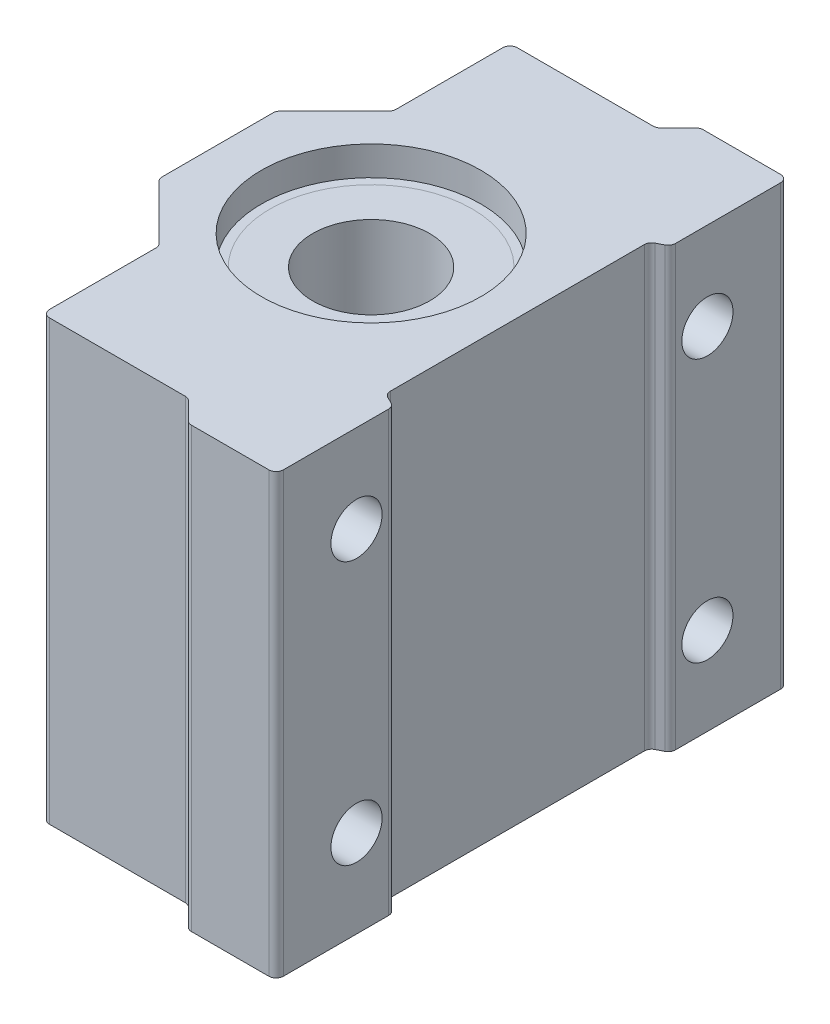
SolidWorks part; units mm, degrees
ref_plane "Front Plane" through (0, 0, 0) normal (0, 0, 1) x (1, 0, 0)
ref_plane "Top Plane" through (0, 0, 0) normal (0, 1, 0) x (1, 0, 0)
ref_plane "Right Plane" through (0, 0, 0) normal (1, 0, 0) x (0, 0, -1)
sketch "Sketch1" plane through (0, 0, 0) normal (0, 1, 0) x (1, 0, 0)
  line L0 (-2.4565, 16.1957) -> (3.5435, 16.1957)
  line L1 (-2.4565, 16.1957) -> (-2.4565, 14.6957) construction
  line L2 (-2.4565, 14.6957) -> (-3.9565, 14.6957) construction
  line L3 (-3.9565, 14.6957) -> (-2.4565, 16.1957)
  line L4 (-3.9565, 14.6957) -> (-13.9565, 14.6957)
  line L5 (-13.9565, 14.6957) -> (-13.9565, 6.6957)
  line L6 (-13.9565, 6.6957) -> (-17.9565, 6.6957) construction
  line L7 (-17.9565, 6.6957) -> (-17.9565, 2.6957) construction
  line L8 (-13.9565, 6.6957) -> (-17.9565, 2.6957)
  line L9 (-17.9565, 2.6957) -> (-17.9565, -5.3043)
  line L10 (-17.9565, -5.3043) -> (-17.9565, -9.3043) construction
  line L11 (-17.9565, -9.3043) -> (-13.9565, -9.3043) construction
  line L12 (-17.9565, -5.3043) -> (-13.9565, -9.3043)
  line L13 (-13.9565, -9.3043) -> (-13.9565, -17.3043)
  line L14 (-13.9565, -17.3043) -> (-3.9565, -17.3043)
  line L15 (-3.9565, -17.3043) -> (-3.9565, -18.8043)
  line L16 (-3.9565, -18.8043) -> (-2.4565, -18.8043) construction
  line L17 (-3.9565, -17.3043) -> (-2.4565, -18.8043)
  line L18 (-2.4565, -18.8043) -> (3.5435, -18.8043)
  line L19 (3.5435, -18.8043) -> (3.5435, -10.8043)
  line L20 (3.5435, 16.1957) -> (3.5435, 8.1957)
  line L21 (3.5435, -10.8043) -> (2.5435, -10.8043) construction
  line L22 (2.5435, -10.8043) -> (2.5435, -10.3043) construction
  line L23 (3.5435, 8.1957) -> (2.5435, 8.1957) construction
  line L24 (2.5435, 8.1957) -> (2.5435, 7.6957) construction
  line L25 (2.5435, -10.3043) -> (3.5435, -10.8043)
  line L26 (2.5435, 7.6957) -> (3.5435, 8.1957)
  line L27 (2.5435, 7.6957) -> (2.5435, -10.3043)
  dimension "D1" = 10
  dimension "D2" = 6
  dimension "D3" = 8
  dimension "D4" = 18
  dimension "D5" = 8
  dimension "D6" = 6
  dimension "D7" = 10
  dimension "D8" = 8
  dimension "D9" = 8
  dimension "D10" = 8
  dimension "D11" = 1.5
  dimension "D12" = 1.5
  dimension "D13" = 1.5
  dimension "D14" = 1.5
  dimension "D15" = 1
  dimension "D16" = 0.5
extrude "Boss-Extrude1" add sketch "Sketch1" along normal blind 30 contours L27 L26 L20 L0 L3 L4 L5 L8 L9 L12 L13 L14 L17 L18 L19 L25
fillet "Fillet1" radius 0.5 16 edges at (-13.9565, 15, 17.3043) (-3.9565, 15, 17.3043) (-2.4565, 15, 18.8043) (3.5435, 15, 18.8043) (3.5435, 15, 10.8043) (2.5435, 15, 10.3043) (2.5435, 15, -7.6957) (3.5435, 15, -8.1957) (3.5435, 15, -16.1957) (-2.4565, 15, -16.1957) (-3.9565, 15, -14.6957) (-13.9565, 15, -14.6957) (-13.9565, 15, -6.6957) (-17.9565, 15, -2.6957) (-17.9565, 15, 5.3043) (-13.9565, 15, 9.3043)
sketch "Sketch2" plane through (0, 0, 0) normal (0, -1, 0) x (1, 0, 0)
  line L0 (3.5435, -10.612) -> (-7.4565, -10.612) construction
  line L1 (3.5435, -15.6957) -> (3.5435, -8.5047) construction
  line L3 (-7.4565, -14.6957) -> (-7.4565, 1.3043) construction
  line L4 (-4.1636, -14.6957) -> (-13.4565, -14.6957) construction
  circle A0 centre (-7.4565, 1.3043) radius 7.5
  dimension "D3" = 15
  dimension "D1" = 11
  dimension "D2" = 16
extrude "Cut-Extrude1" cut sketch "Sketch2" against normal blind 30
ref_plane "Plane1" through (0, 2, 0) normal (0, 1, 0) x (1, 0, 0)
sketch "Sketch4" plane through (0, 2, 0) normal (0, 1, 0) x (1, 0, 0)
  circle A0 centre (-7.4565, -1.3043) radius 7.5
  circle A1 centre (-7.4565, -1.3043) radius 6.9114
extrude "Boss-Extrude2" add sketch "Sketch4" along normal blind 26
sketch "Sketch5" plane through (0, 2, 0) normal (0, 1, 0) x (1, 0, 0)
  circle A0 centre (-7.4565, -1.3043) radius 6.9114
  circle A1 centre (-7.4565, -1.3043) radius 4
  dimension "D1" = 8
extrude "Boss-Extrude3" add sketch "Sketch5" along normal blind 26 separate body
sketch "Sketch6" plane through (-13.9565, 0, 0) normal (-1, 0, 0) x (0, 0, 1)
  line L0 (1.3043, 30) -> (1.3043, 0) construction
  line L2 (18.6579, 15) -> (-16.0492, 15) construction
  line L5 (18.6579, 0) -> (18.6579, 30) construction
  line L6 (-10.6957, 24) -> (13.3043, 24) construction
  line L7 (-10.6957, 24) -> (-10.6957, 6) construction
  line L8 (-10.6957, 6) -> (13.3043, 6) construction
  line L9 (13.3043, 24) -> (13.3043, 6) construction
  line L10 (-10.6957, 24) -> (13.3043, 6) construction
  line L11 (-10.6957, 6) -> (13.3043, 24) construction
  line L12 (-16.0492, 30) -> (-16.0492, 0) construction
  line L13 (-2.4885, 30) -> (5.0972, 30) construction
  line L14 (-2.4885, 0) -> (5.0972, 0) construction
  circle A0 centre (13.3043, 24) radius 1.75
  circle A1 centre (13.3043, 6) radius 1.75
  circle A2 centre (-10.6957, 6) radius 1.75
  circle A3 centre (-10.6957, 24) radius 1.75
  point P11 (1.3043, 15)
  dimension "D3" = 3.5
  dimension "D4" = 3.5
  dimension "D5" = 3.5
  dimension "D6" = 3.5
  dimension "D1" = 18
  dimension "D2" = 24
extrude "Cut-Extrude2" cut sketch "Sketch6" against normal blind 26
